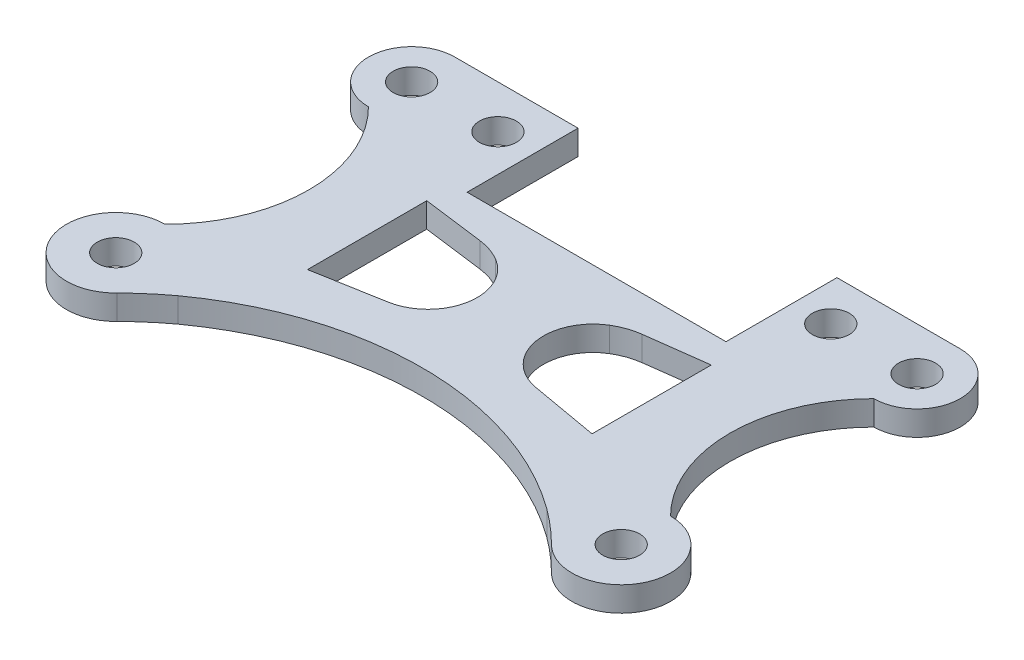
SolidWorks part; units mm, degrees
material "Cast Alloy Steel"
ref_plane "Front Plane" through (0, 0, 0) normal (0, 0, 1) x (1, 0, 0)
ref_plane "Top Plane" through (0, 0, 0) normal (0, 1, 0) x (1, 0, 0)
ref_plane "Right Plane" through (0, 0, 0) normal (1, 0, 0) x (0, 0, -1)
sketch "Sketch1" plane through (0, 0, 0) normal (0, 1, 0) x (1, 0, 0)
  line L0 (10.5, 14) -> (10.5, 5)
  line L1 (-20.5, 14) -> (20.5, 14)
  line L2 (-20.5, 14) -> (-20.5, -14)
  line L3 (-20.5, -14) -> (20.5, -14)
  line L4 (20.5, 14) -> (20.5, -14)
  line L5 (-20.5, 14) -> (20.5, -14) construction
  line L6 (-20.5, -14) -> (20.5, 14) construction
  line L7 (10.5, 5) -> (-10.5, 5)
  line L8 (-10.5, 5) -> (-10.5, 14)
  line L9 (-10.5, 14) -> (-20.5, 14)
  line L10 (10.5, 14) -> (20.5, 14)
  circle A0 centre (20.5, 10.5) radius 3.5
  circle A1 centre (20.5, 10.5) radius 1.5
  circle A2 centre (13.5, 10.5) radius 1.5
  arc A3 (-20.5, -14) -> (20.5, -14) centre (0, -35.4884) cw
  point P0 (0, 0)
  point P16 (0, 0)
  point P17 (0, 0)
  dimension "D3" = 7
  dimension "D5" = 10
  dimension "D10" = 3
  dimension "D1" = 41
  dimension "D2" = 28
  dimension "D4" = 3.5
  dimension "D6" = 10
  dimension "D7" = 9
  dimension "D8" = 3.5
  dimension "D9" = 3
extrude "Boss-Extrude1" add sketch "Sketch1" along normal blind 2 contours L2 A3 L4 A0 L1 L0 L7 L8 A2 | A1 L4 A0 | A1 L4 A0
sketch "Sketch2" plane through (0, 2, 0) normal (0, 1, 0) x (1, 0, 0)
  line L0 (-20.5, 14) -> (-20.5, -14) construction
  line L1 (-20.5, 14) -> (-10.5, 14) construction
  circle A0 centre (-20.5, 10.5) radius 3.5
  dimension "D2" = 7
  dimension "D1" = 3.5
extrude "Boss-Extrude2" add sketch "Sketch2" against normal blind 2
sketch "Sketch3" plane through (0, 2, 0) normal (0, 1, 0) x (1, 0, 0)
  circle A0 centre (-20.5, 10.5) radius 1.5
  dimension "D1" = 3
extrude "Cut-Extrude1" cut sketch "Sketch3" against normal blind 2
sketch "Sketch4" plane through (0, 2, 0) normal (0, 1, 0) x (1, 0, 0)
  line L0 (-20.5, 14) -> (-10.5, 14) construction
  line L1 (-10.5, 5) -> (-10.5, 14) construction
  circle A0 centre (-13.5, 10.5) radius 1.5
  dimension "D3" = 3
  dimension "D1" = 3.5
  dimension "D2" = 3
extrude "Cut-Extrude2" cut sketch "Sketch4" against normal blind 2
sketch "Sketch5" plane through (0, 2, 0) normal (0, 1, 0) x (1, 0, 0)
  line L0 (-20.5, 7) -> (-20.5, -14) construction
  line L1 (20.5, 7) -> (20.5, -14) construction
  line L2 (-20.5, -14) -> (20.5, -14)
  line L10 (-10.5, 14) -> (-20.5, 14)
  line L11 (-20.5, 7) -> (-20.5, -14)
  line L12 (20.5, -14) -> (20.5, 7)
  line L13 (20.5, 14) -> (10.5, 14)
  line L14 (10.5, 14) -> (10.5, 5)
  line L15 (10.5, 5) -> (-10.5, 5)
  line L16 (-10.5, 5) -> (-10.5, 14)
  circle A1 centre (20.5, 10.5) radius 1.5 construction
  arc A6 (-20.5, 14) -> (-20.5, 7) centre (-20.5, 10.5) ccw
  arc A7 (20.5, -14) -> (-20.5, -14) centre (0, -35.4884) ccw
  arc A8 (20.5, 7) -> (20.5, 14) centre (20.5, 10.5) ccw
  arc A10 (20.5, -14) -> (-20.5, -14) centre (0, -35.4884) ccw
  point P0 (-20.5, -9)
  point P6 (20.5, -13.5)
  dimension "D2" = 24
  dimension "D3" = 0
  dimension "D1" = 16
extrude "Boss-Extrude3" add sketch "Sketch5" against normal blind 2 contours L2 A10
sketch "Sketch8" plane through (0, 2, 0) normal (0, 1, 0) x (1, 0, 0)
  line L0 (20.5, 7) -> (20.5, -14) construction
  circle A0 centre (20.5, -13.5) radius 4
  circle A1 centre (20.5, 10.5) radius 1.5 construction
  dimension "D1" = 24
  dimension "D2" = 8
extrude "Boss-Extrude5" add sketch "Sketch8" against normal blind 2
sketch "Sketch9" plane through (0, 2, 0) normal (0, 1, 0) x (1, 0, 0)
  circle A0 centre (20.5, -13.5) radius 1.5
  dimension "D1" = 3
extrude "Cut-Extrude4" cut sketch "Sketch9" against normal blind 2
sketch "Sketch10" plane through (0, 2, 0) normal (0, 1, 0) x (1, 0, 0)
  line L0 (20.5, 7) -> (20.5, -9.5)
  arc A0 (20.5, -9.5) -> (20.5, 7) centre (28.75, -1.25) cw
extrude "Cut-Extrude5" cut sketch "Sketch10" against normal blind 2
mirror "Mirror12" about plane through (0, 0, 0) normal (1, 0, 0) of "Cut-Extrude5", "Boss-Extrude5", "Cut-Extrude4"
sketch "Sketch12" plane through (0, 2, 0) normal (0, 1, 0) x (1, 0, 0)
  line L6 (-16.5314, -14) -> (16.5314, -14)
  line L7 (20.5, 14) -> (10.5, 14)
  line L8 (10.5, 14) -> (10.5, 5)
  line L9 (10.5, 5) -> (-10.5, 5)
  line L10 (-10.5, 5) -> (-10.5, 14)
  line L11 (-10.5, 14) -> (-20.5, 14)
  line L12 (-16.5314, -14) -> (16.5314, -14)
  arc A0 (-17.7528, -16.4074) -> (17.6122, -16.2677) centre (0, -34.1458) cw
  arc A1 (-20.5, -9.5) -> (-16.5314, -14) centre (-20.5, -13.5) ccw construction
  arc A2 (16.5314, -14) -> (20.5, -9.5) centre (20.5, -13.5) ccw construction
  arc A9 (-20.5, 14) -> (-20.5, 7) centre (-20.5, 10.5) ccw
  arc A10 (-20.5, -9.5) -> (-20.5, 7) centre (-28.75, -1.25) ccw
  arc A11 (-20.5, -9.5) -> (-16.5314, -14) centre (-20.5, -13.5) ccw
  arc A12 (16.5314, -14) -> (20.5, -9.5) centre (20.5, -13.5) ccw
  arc A13 (20.5, 7) -> (20.5, -9.5) centre (28.75, -1.25) ccw
  arc A14 (20.5, 7) -> (20.5, 14) centre (20.5, 10.5) ccw
  arc A17 (-17.7528, -16.4074) -> (-16.5314, -14) centre (-20.5, -13.5) ccw
  arc A18 (16.5314, -14) -> (17.6122, -16.2677) centre (20.5, -13.5) ccw
  dimension "D1" = 0
extrude "Boss-Extrude12" add sketch "Sketch12" against normal blind 2 contours A2 A0 A9 | A9 A0 A10
sketch "Sketch20" plane through (0, 2, 0) normal (0, 1, 0) x (1, 0, 0)
  line L0 (14.9653, -14) -> (-14.9653, -14)
  arc A0 (-14.9653, -14) -> (14.9653, -14) centre (0, -34.6584) cw
extrude "Cut-Extrude11" cut sketch "Sketch20" against normal blind 2
sketch "Sketch21" plane through (0, 2, 0) normal (0, 1, 0) x (1, 0, 0)
  line L0 (11.5397, 2.7648) -> (2.2069, 1.5519)
  line L3 (11.5397, -2.5923) -> (11.5397, 2.7648)
  line L4 (11.5397, -2.5923) -> (11.5397, -6.905)
  line L5 (11.5397, -6.905) -> (2.2069, -5.254)
  line L6 (2.2069, -5.254) -> (2.2069, 1.5519)
extrude "Cut-Extrude15" cut sketch "Sketch21" against normal blind 19
fillet "Fillet1" radius 5 1 edges at (2.2069, 1, -1.5519)
fillet "Fillet2" radius 4 1 edges at (2.2069, 1, 5.254)
mirror "Mirror13" about plane through (0, 0, 0) normal (1, 0, 0) of "Fillet1", "Cut-Extrude15", "Fillet2"
